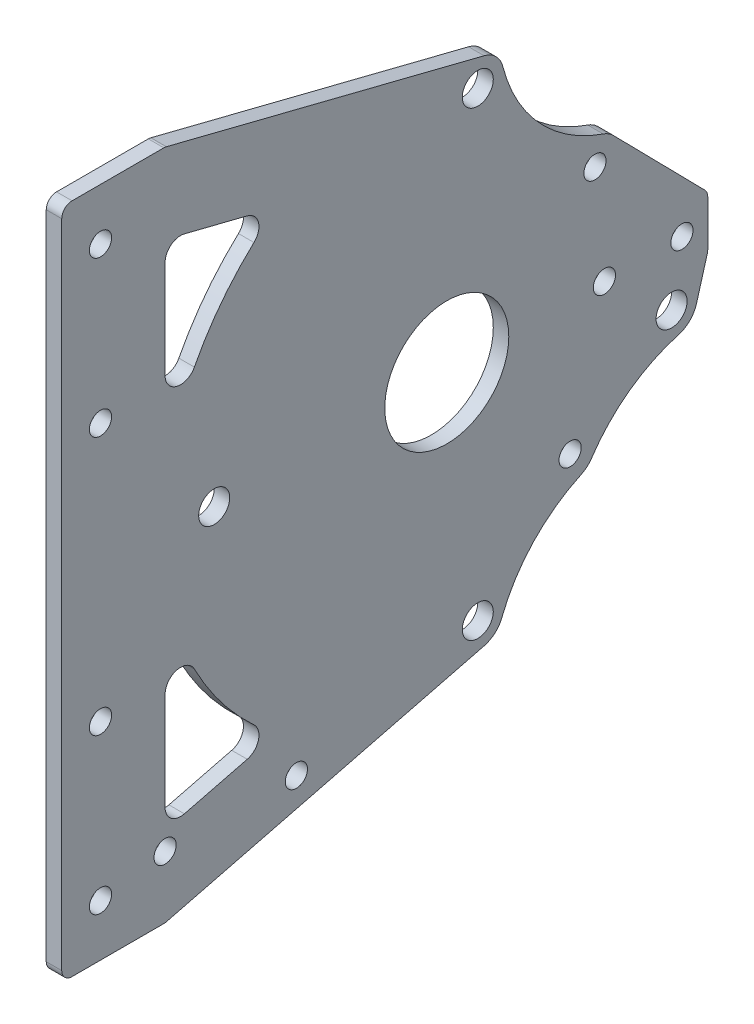
SolidWorks part; units mm, degrees
material "5052-H34"
ref_plane "正面" through (0, 0, 0) normal (0, 0, 1) x (1, 0, 0)
ref_plane "平面" through (0, 0, 0) normal (0, 1, 0) x (1, 0, 0)
ref_plane "右側面" through (0, 0, 0) normal (1, 0, 0) x (0, 0, -1)
sketch "ｽｹｯﾁ1" plane through (0, 0, 0) normal (1, 0, 0) x (0, 0, -1)
  line L0 (125, 65) -> (117.85, 65) construction
  line L1 (0, 0) -> (20, 0)
  line L2 (0, 0) -> (0, 130)
  line L3 (0, 130) -> (20, 130)
  line L5 (74.5, 65) -> (74.5, 53) construction
  line L6 (80.5, 65) -> (80.5, 20.4) construction
  line L7 (74.5, 53.7) -> (118, 53.7) construction
  line L8 (20, 130) -> (81.7216, 114.4485)
  line L9 (20, 0) -> (81.7216, 15.5515)
  line L10 (74.5, 65) -> (103.1703, 85.0752) construction
  line L11 (74.5, 65) -> (98.3699, 39.4026) construction
  line L12 (125, 70) -> (125, 60)
  line L13 (125, 60) -> (122.8076, 52.3264)
  line L14 (125, 70) -> (106.7361, 88.5802)
  line L15 (117.85, 65) -> (113.611, 65) construction
  line L16 (113.611, 65) -> (0, 65) construction
  line L17 (0, 12) -> (67.6261, 12) construction
  circle A0 centre (7.5, 120) radius 2.15
  circle A1 centre (7.5, 90) radius 2.15
  circle A2 centre (7.5, 40) radius 2.15
  circle A3 centre (7.5, 10) radius 2.15
  circle A4 centre (74.5, 65) radius 12
  circle A5 centre (29.5, 65) radius 3
  circle A6 centre (80.5, 20.4) radius 3
  circle A7 centre (118, 53.7) radius 3
  circle A8 centre (80.5, 109.6) radius 3
  arc A9 (85.3461, 110.831) -> (81.7216, 114.4485) centre (80.5, 109.6) ccw
  arc A10 (119.3587, 48.8881) -> (122.8076, 52.3264) centre (118, 53.7) ccw
  arc A11 (81.7216, 15.5515) -> (85.1565, 18.5787) centre (80.5, 20.4) ccw
  circle A12 centre (74.5, 65) radius 20 construction
  arc A15 (106.7361, 88.5802) -> (104.7778, 89.8097) centre (103.1703, 85.0752) ccw
  circle A16 centre (103.1703, 85.0752) radius 2.15
  arc A17 (85.3461, 110.831) -> (104.7778, 89.8097) centre (114.4226, 118.2171) ccw
  arc A18 (113.611, 65) -> (108.1554, 84.6897) centre (138.0661, 82.3766) cw construction
  arc A19 (100.4736, 34.8667) -> (102.5329, 36.6333) centre (98.3699, 39.4026) ccw
  circle A20 centre (98.3699, 39.4026) radius 2.15
  arc A22 (85.1565, 18.5787) -> (100.4736, 34.8667) centre (113.0955, 7.6511) cw
  arc A23 (119.3587, 48.8881) -> (102.5329, 36.6333) centre (127.511, 20.017) ccw
  circle A24 centre (105, 65) radius 2.15
  circle A25 centre (120, 65) radius 2.15
  arc A26 (122.8076, 52.3264) -> (120.8666, 57.7967) centre (118, 53.7) ccw construction
  arc A27 (120.8666, 57.7967) -> (113.611, 65) centre (138.0661, 82.3766) cw construction
  arc A28 (108.1554, 84.6897) -> (106.7361, 88.5802) centre (103.1703, 85.0752) ccw construction
  circle A29 centre (20, 12) radius 2.15
  circle A30 centre (45.4, 12) radius 2.15
  dimension "D3" = 30
  dimension "D4" = 4.3
  dimension "D5" = 7.5
  dimension "D6" = 10
  dimension "D7" = 6
  dimension "D8" = 45
  dimension "D10" = 24
  dimension "D11" = 74.5
  dimension "D12" = 44.6
  dimension "D14" = 43.5
  dimension "D15" = 44.6
  dimension "D16" = 10
  dimension "D17" = 40
  dimension "D18" = 30
  dimension "D20" = 10
  dimension "D23" = 47
  dimension "D24" = 4.3
  dimension "D26" = 30
  dimension "D27" = 15
  dimension "D28" = 105
  dimension "D30" = 25.4
  dimension "D31" = 4.3
  dimension "D32" = 20
  dimension "D1" = 130
  dimension "D9" = 6
  dimension "D13" = 11.3
  dimension "D19" = 20
  dimension "D21" = 20
  dimension "D22" = 35
  dimension "D25" = 35
  dimension "D29" = 5
  dimension "D33" = 12
extrude "ﾎﾞｽ - 押し出し1" add sketch "ｽｹｯﾁ1" along normal blind 3
sketch "ｽｹｯﾁ2" plane through (3, 0, 0) normal (1, 0, 0) x (0, 0, -1)
  line L0 (20, 114.5312) -> (20, 72.3993)
  line L1 (20, 114.5312) -> (41.614, 109.0853)
  line L2 (81.7216, 114.4485) -> (20, 130) construction
  line L3 (20, 15.4688) -> (41.614, 20.9147)
  line L4 (20, 0) -> (81.7216, 15.5515) construction
  line L7 (20, 57.6007) -> (20, 15.4688)
  line L9 (0, 130) -> (0, 0) construction
  arc A0 (20, 57.6007) -> (41.614, 20.9147) centre (74.5, 65) ccw
  arc A3 (41.614, 109.0853) -> (20, 72.3993) centre (74.5, 65) ccw
  dimension "D3" = 110
  dimension "D1" = 15
  dimension "D2" = 15
  dimension "D4" = 20
extrude "ｶｯﾄ - 押し出し1" cut sketch "ｽｹｯﾁ2" against normal up to surface (3 mm away) up to face at (0, 62.54, -79.7999)
fillet "ﾌｨﾚｯﾄ1" radius 2 4 edges at (1.5, 0, -20) (1.5, 0, 0) (1.5, 130, -20) (1.5, 130, 0)
fillet "ﾌｨﾚｯﾄ2" radius 2 2 edges at (1.5, 60, -125) (1.5, 70, -125)
fillet "ﾌｨﾚｯﾄ3" radius 3 6 edges at (1.5, 15.4688, -20) (1.5, 20.9147, -41.614) (1.5, 57.6007, -20) (1.5, 72.3993, -20) (1.5, 109.0853, -41.614) (1.5, 114.5312, -20)
